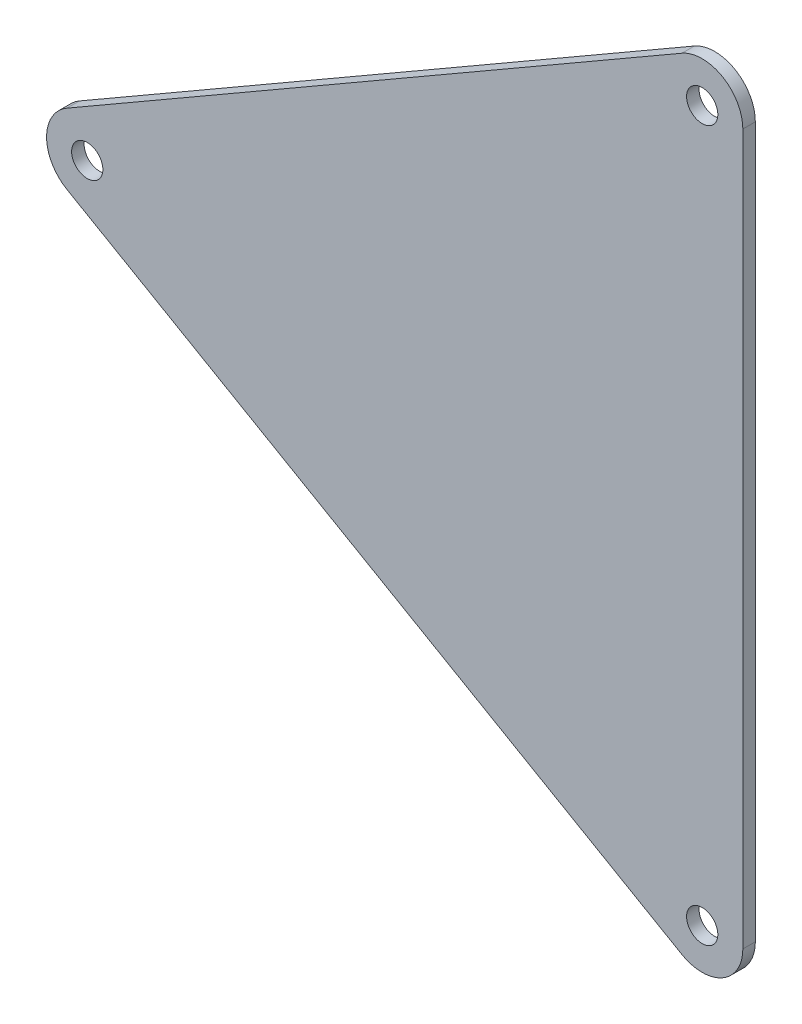
SolidWorks part; units mm, degrees
material "1060 Alloy"
ref_plane "Front Plane" through (0, 0, 0) normal (0, 0, 1) x (1, 0, 0)
ref_plane "Top Plane" through (0, 0, 0) normal (0, 1, 0) x (1, 0, 0)
ref_plane "Right Plane" through (0, 0, 0) normal (1, 0, 0) x (0, 0, -1)
sketch "Sketch1" plane through (0, 0, 0) normal (0, 0, 1) x (1, 0, 0)
  line L0 (248.5, 0) -> (353.0314, 60.3512) construction
  line L1 (248.5, 0) -> (351.6554, -59.5568) construction
  line L2 (248.5, 0) -> (359.7731, 0) construction
  line L3 (245.25, -5.6292) -> (343.6304, -62.4291)
  line L4 (245.25, 5.6292) -> (343.6304, 62.4291)
  line L5 (353.3804, -56.8) -> (353.3804, 56.8)
  line L7 (254.9721, 3.7689) -> (255, 3.7528)
  line L10 (251.75, 5.6292) -> (344.1046, -47.6918) construction
  circle A0 centre (0, 0) radius 345 construction
  circle A1 centre (0, 0) radius 255 construction
  circle A3 centre (248.5, 0) radius 2.5
  circle A4 centre (346.8804, 56.8) radius 6.5 construction
  circle A5 centre (248.5, 0) radius 6.5 construction
  circle A6 centre (346.8804, -56.8) radius 6.5 construction
  circle A7 centre (346.8804, -56.8) radius 2.5
  circle A8 centre (346.8804, 56.8) radius 2.5
  arc A9 (245.25, 5.6292) -> (245.25, -5.6292) centre (248.5, 0) ccw
  arc A10 (343.6304, -62.4291) -> (353.3804, -56.8) centre (346.8804, -56.8) ccw
  arc A11 (343.6304, 62.4291) -> (353.3804, 56.8) centre (346.8804, 56.8) cw
  arc A15 (344.1046, -47.6918) -> (344.1046, -47.6918) centre (344.1046, -47.6918) ccw construction
  point P26 (257.7758, -2.1501)
  point P28 (344.1046, 47.6918)
  point P35 (340.3804, -56.8)
  point P36 (340.3804, 56.8)
  dimension "D1" = 690
  dimension "D2" = 510
  dimension "D3" = 13
  dimension "D6" = 13
  dimension "D7" = 13
  dimension "D4" = 30
  dimension "D5" = 30
  dimension "D9" = 13
extrude "Boss-Extrude2" add sketch "Sketch1" along normal blind 2
